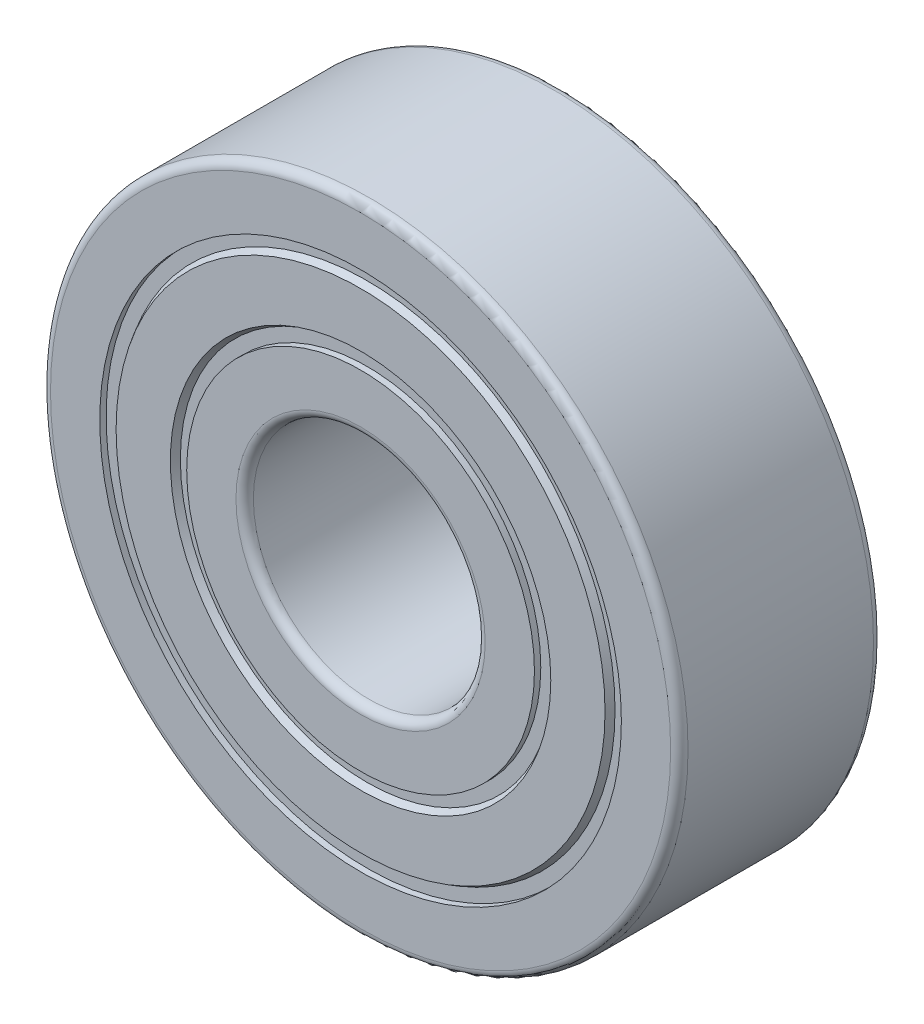
SolidWorks part; units mm, degrees
ref_plane "Plane1" through (0, 0, 0) normal (0, 0, 1) x (1, 0, 0)
ref_plane "Plane2" through (0, 0, 0) normal (0, 1, 0) x (1, 0, 0)
ref_plane "Plane3" through (0, 0, 0) normal (1, 0, 0) x (0, 0, -1)
sketch "Sketch2" plane through (0, 0, 0) normal (0, 1, 0) x (1, 0, 0)
  line L0 (0, -19) -> (0, 31) construction
  line L1 (-9, 0) -> (-9, -0.2188)
  line L2 (-4.3, -7) -> (-6, -7)
  line L3 (-4, -6.7) -> (-4, -0.3)
  line L4 (-4.3, 0) -> (-6, 0)
  line L5 (-11, -6.7) -> (-11, -0.3)
  line L6 (-9, -7) -> (-9, -6.7812)
  line L7 (-9, 0) -> (-10.7, 0)
  line L8 (-9, -7) -> (-10.7, -7)
  line L9 (-11, -3.5) -> (-4, -3.5) construction
  line L10 (-9, -0.2188) -> (-8.5625, -0.2188)
  line L11 (-9, -6.7812) -> (-8.5625, -6.7812)
  line L12 (-8.5625, -0.2188) -> (-8.4362, 0)
  line L13 (-8.5625, -6.7812) -> (-8.4362, -7)
  line L14 (-6, 0) -> (-6, -0.2188)
  line L15 (-6, -7) -> (-6, -6.7812)
  line L16 (-8.4362, -7) -> (-6.5638, -7)
  line L17 (-8.4362, 0) -> (-6.5638, 0)
  line L18 (-6, -0.2188) -> (-6.4375, -0.2188)
  line L19 (-6, -6.7812) -> (-6.4375, -6.7812)
  line L20 (-6.4375, -0.2188) -> (-6.5638, 0)
  line L21 (-6.4375, -6.7812) -> (-6.5638, -7)
  line L26 (-4.3, -7) -> (-4.2, -7) construction
  line L27 (-4.3, 0) -> (-4.2, 0) construction
  line L28 (-4, -6.8) -> (-4, -6.7) construction
  line L29 (-4, -0.2) -> (-4, -0.3) construction
  line L30 (-11, -6.7) -> (-11, -6.8) construction
  line L31 (-10.8, -7) -> (-10.7, -7) construction
  line L32 (-11, -0.3) -> (-11, -0.2) construction
  line L33 (-10.8, 0) -> (-10.7, 0) construction
  arc A0 (-11, -0.3) -> (-10.7, 0) centre (-10.7, -0.3) cw
  arc A1 (-11, -6.7) -> (-10.7, -7) centre (-10.7, -6.7) ccw
  arc A2 (-4, -6.7) -> (-4.3, -7) centre (-4.3, -6.7) cw
  arc A3 (-4.3, 0) -> (-4, -0.3) centre (-4.3, -0.3) cw
  arc A4 (-4, -6.8) -> (-4.2, -7) centre (-4.2, -6.8) cw construction
  arc A5 (-4, -0.2) -> (-4.2, 0) centre (-4.2, -0.2) ccw construction
  arc A6 (-10.8, -7) -> (-11, -6.8) centre (-10.8, -6.8) cw construction
  arc A7 (-10.8, 0) -> (-11, -0.2) centre (-10.8, -0.2) ccw construction
  circle A8 centre (-7.5, -3.5) radius 2.1875
  dimension "r" = 0.3
  dimension "BallDia" = 4.375
  dimension "B" = 7
  dimension "D4" = 6.5625
  dimension "ID" = 8
  dimension "OD" = 22
  dimension "D5" = 6.5625
  dimension "OR-ID" = 18
  dimension "IR-OD" = 12
  dimension "Shield-OD" = 0.4375
  dimension "D9" = 60
  dimension "Shield-ID" = 0.4375
  dimension "D11" = 60
revolve "Base-Revolve" add sketch "Sketch2" angle 360 about L0
equation "\"D5@Sketch2\"=\"B@Sketch2\" * .9375"
equation "\"D4@Sketch2\" = \"D5@Sketch2\""
equation "\"BallDia@Sketch2\" = \"B@Sketch2\" * .625"
equation "\"Shield-OD@Sketch2\" = (\"OD@Sketch2\"-\"ID@Sketch2\") * 0.03125"
equation "\"Shield-ID@Sketch2\" = \"Shield-OD@Sketch2\""
